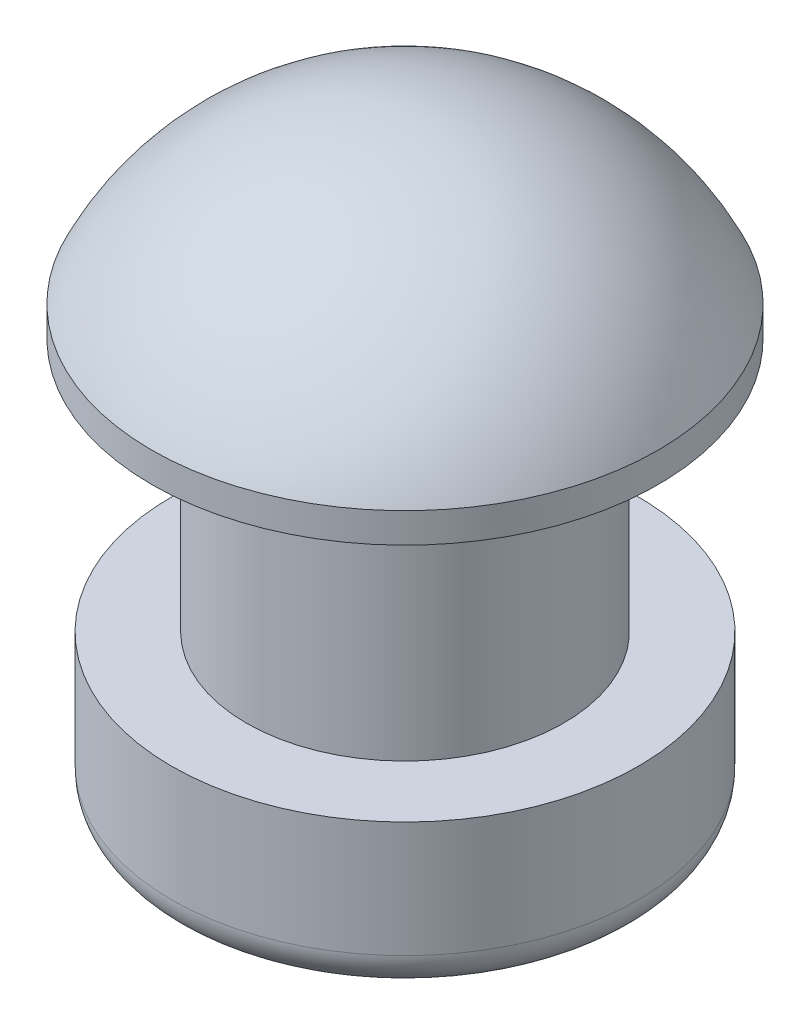
SolidWorks part; units mm, degrees
ref_plane "Front Plane" through (0, 0, 0) normal (0, 0, 1) x (1, 0, 0)
ref_plane "Top Plane" through (0, 0, 0) normal (0, 1, 0) x (1, 0, 0)
ref_plane "Right Plane" through (0, 0, 0) normal (1, 0, 0) x (0, 0, -1)
sketch "Sketch1" plane through (0, 0, 0) normal (0, 0, 1) x (1, 0, 0)
  line L0 (0, 5.3795) -> (0, -5.8072) construction
  line L1 (0, 5.08) -> (0, 0)
  line L2 (2.159, -1.778) -> (2.159, -3.048)
  line L3 (2.159, -3.048) -> (3.175, -3.048)
  line L4 (3.175, -3.048) -> (3.175, -0.9652)
  line L5 (3.175, -0.9652) -> (2.159, -0.9652)
  line L6 (2.159, -0.9652) -> (2.159, 2.4892)
  line L7 (2.159, 2.4892) -> (3.4458, 2.4892)
  line L8 (3.4458, 2.4892) -> (3.4458, 2.8956)
  line L9 (-11.2374, 0) -> (16.0264, 0) construction
  arc A1 (0, 5.08) -> (3.4458, 2.8956) centre (0, 1.27) cw
  arc A2 (0, 0) -> (2.159, -1.778) centre (-0.9989, -3.4128) cw
  dimension "D6" = 3.175
  dimension "D7" = 8.128
  dimension "D8" = 3.81
  dimension "D4" = 1.27
  dimension "D10" = 2.159
  dimension "D11" = 3.556
  dimension "D5" = 3.048
  dimension "D1" = 0.4064
  dimension "D2" = 3.4544
  dimension "D3" = 2.159
  dimension "D9" = 2.0828
revolve "Revolve1" add sketch "Sketch1" angle 360 about L0
fillet "Fillet1" radius 0.508 1 edges at (0, -3.048, 3.175)
